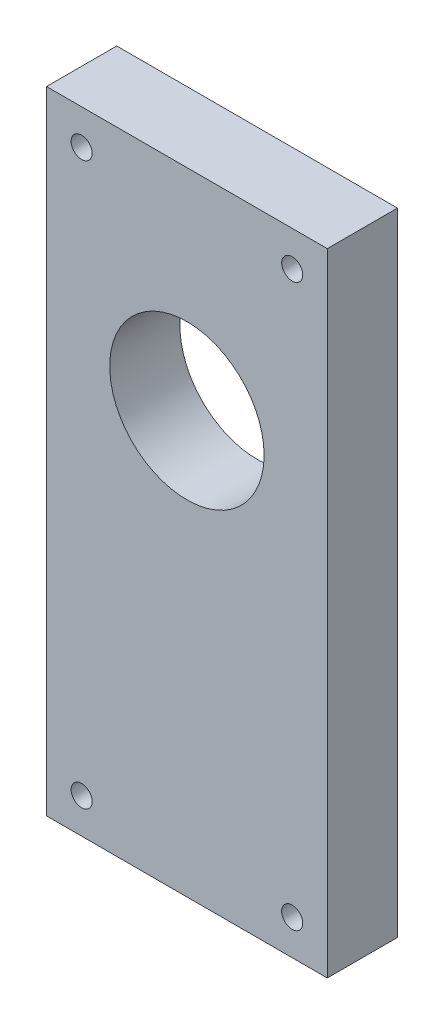
SolidWorks part; units mm, degrees
ref_plane "Front Plane" through (0, 0, 0) normal (0, 0, 1) x (1, 0, 0)
ref_plane "Top Plane" through (0, 0, 0) normal (0, 1, 0) x (1, 0, 0)
ref_plane "Right Plane" through (0, 0, 0) normal (1, 0, 0) x (0, 0, -1)
sketch "Sketch1" plane through (0, 0, 0) normal (0, 0, 1) x (1, 0, 0)
  line L0 (-99.1891, 34.1148) -> (-99.1891, 39.1148) construction
  line L1 (-104.1891, 39.1148) -> (-84.1891, 39.1148)
  line L2 (-104.1891, 39.1148) -> (-104.1891, -50.8852)
  line L3 (-104.1891, -50.8852) -> (-84.1891, -50.8852)
  line L4 (-84.1891, 39.1148) -> (-84.1891, -50.8852)
  line L5 (-99.1891, 34.1148) -> (-104.1891, 34.1148) construction
  line L6 (-99.1891, -45.8852) -> (-104.1891, -45.8852) construction
  line L7 (-99.1891, -45.8852) -> (-99.1891, -50.8852) construction
  line L8 (-94.1891, -50.8852) -> (-94.1891, 39.1148) construction
  line L9 (-99.1891, -45.8852) -> (-94.1891, -45.8852) construction
  line L11 (-84.1891, -5.8852) -> (-104.1891, -5.8852) construction
  circle A0 centre (-84.1891, 9.1148) radius 11
  circle A3 centre (-99.1891, 34.1148) radius 1.5
  circle A4 centre (-99.1891, -45.8852) radius 1.5
  circle A5 centre (-84.1891, 9.1148) radius 4 construction
  point P16 (0, 0)
  point P19 (0, 0)
  dimension "D1" = 22
  dimension "D4" = 3
  dimension "D8" = 8
  dimension "D6" = 15
  dimension "D7" = 80
  dimension "D2" = 10
  dimension "D9" = 10
  dimension "D3" = 5
extrude "Boss-Extrude1" add sketch "Sketch1" along normal blind 10 contours A0 L4 L1 L8 L3
mirror "Mirror1" about plane through (-84.1891, 0, 10) normal (1, 0, 0) of "Boss-Extrude1"
equation "\"D2@Sketch1\"=20/2"
